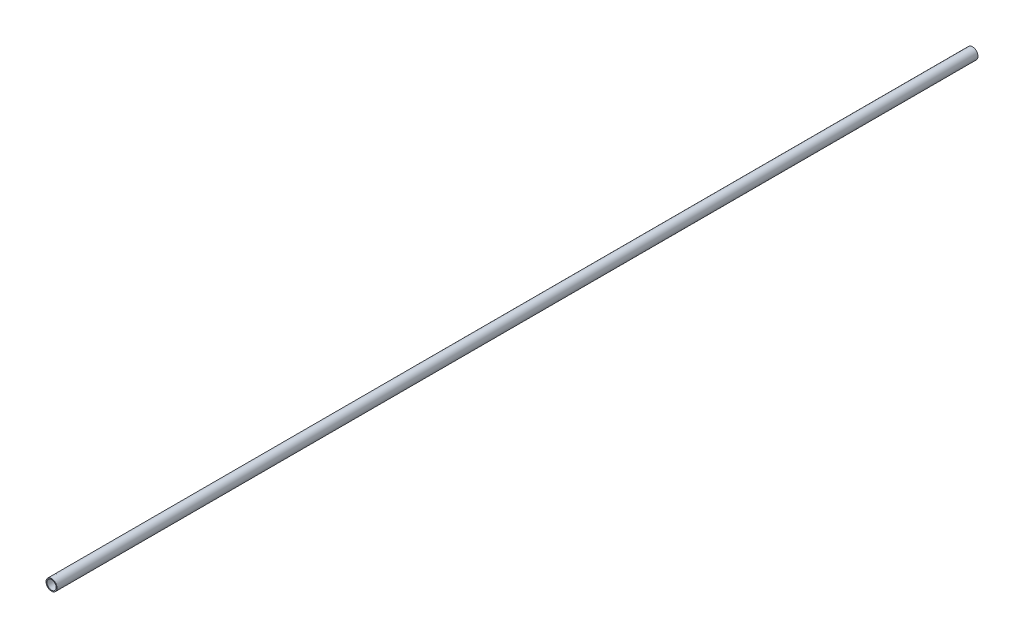
SolidWorks part; units mm, degrees
material "5052-O"
ref_plane "正面" through (0, 0, 0) normal (0, 0, 1) x (1, 0, 0)
ref_plane "平面" through (0, 0, 0) normal (0, 1, 0) x (1, 0, 0)
ref_plane "右側面" through (0, 0, 0) normal (1, 0, 0) x (0, 0, -1)
sketch "ｽｹｯﾁ1" plane through (0, 0, 0) normal (0, 0, 1) x (1, 0, 0)
  circle A0 centre (0, 0) radius 6
  circle A1 centre (0, 0) radius 5
  dimension "D1" = 12
  dimension "D2" = 10
extrude "ﾎﾞｽ - 押し出し1" add sketch "ｽｹｯﾁ1" along normal blind 1000
